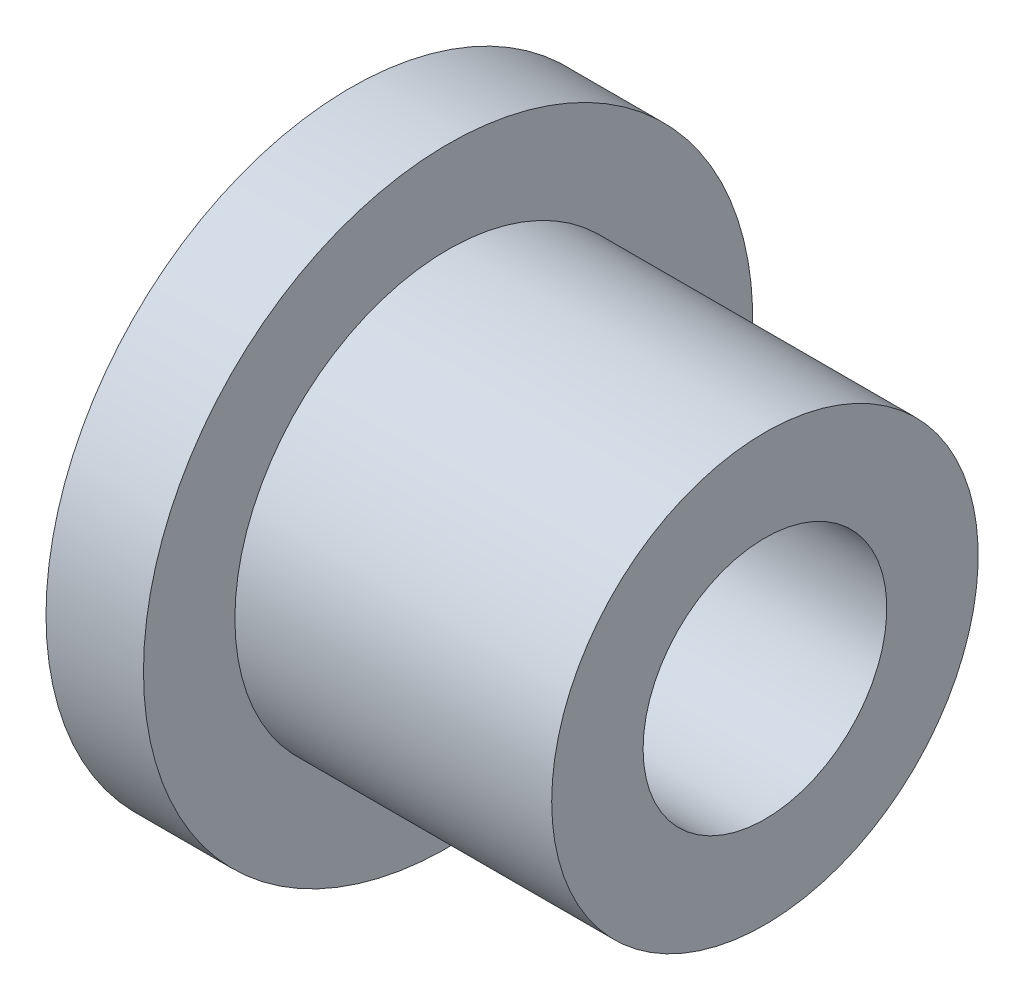
SolidWorks part; units mm, degrees
ref_plane "Front Plane" through (0, 0, 0) normal (0, 0, 1) x (1, 0, 0)
ref_plane "Top Plane" through (0, 0, 0) normal (0, 1, 0) x (1, 0, 0)
ref_plane "Right Plane" through (0, 0, 0) normal (1, 0, 0) x (0, 0, -1)
sketch "Sketch1" plane through (0, 0, 0) normal (0, 0, 1) x (1, 0, 0)
  line L0 (-24.9161, -4.3679) -> (29.1655, -4.3679) construction
  line L1 (2.1247, -21.987) -> (2.1247, 13.2511) construction
  line L2 (2.1247, 5.6321) -> (-31.8753, 5.6321)
  line L3 (-31.8753, 5.6321) -> (-31.8753, 20.6321)
  line L4 (-31.8753, 20.6321) -> (-23.8753, 20.6321)
  line L5 (-23.8753, 20.6321) -> (-23.8753, 13.1321)
  line L6 (-23.8753, 13.1321) -> (2.1247, 13.1321)
  line L7 (2.1247, 13.1321) -> (2.1247, 5.6321)
  point P3 (2.1247, -4.3679)
  point P6 (2.1247, -4.3679)
  dimension "D1" = 8
  dimension "D2" = 26
  dimension "D3" = 10
  dimension "D4" = 25
  dimension "D5" = 17.5
revolve "Revolve1" add sketch "Sketch1" angle 360 about L0
